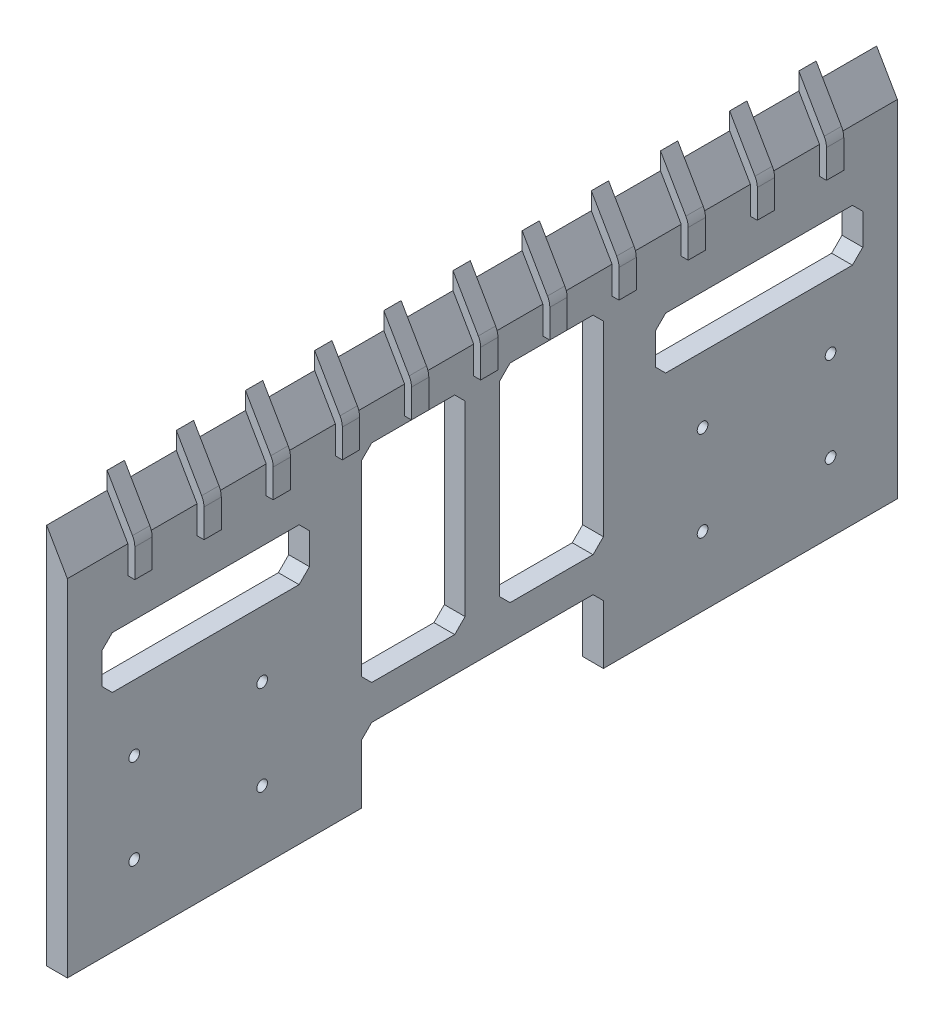
SolidWorks part; units mm, degrees
ref_plane "前视基准面" through (0, 0, 0) normal (0, 0, 1) x (1, 0, 0)
ref_plane "上视基准面" through (0, 0, 0) normal (0, 1, 0) x (1, 0, 0)
ref_plane "右视基准面" through (0, 0, 0) normal (1, 0, 0) x (0, 0, -1)
sketch "草图1" plane through (0, 0, 0) normal (1, 0, 0) x (0, 0, -1)
  line L1 (0, 0) -> (240, 0)
  line L2 (0, 0) -> (0, -100)
  line L3 (0, -100) -> (240, -100)
  line L4 (240, 0) -> (240, -100)
  dimension "D1" = 240
  dimension "D2" = 100
extrude "凸台-拉伸1" add sketch "草图1" along normal blind 6
sketch "草图2" plane through (6, 0, 0) normal (1, 0, 0) x (0, 0, -1)
  line L0 (0, 0) -> (0, -100) construction
  line L1 (19.3235, -54) -> (56.3235, -54) construction
  line L2 (19.3235, -54) -> (19.3235, -80) construction
  line L3 (19.3235, -80) -> (56.3235, -80) construction
  line L4 (56.3235, -54) -> (56.3235, -80) construction
  line L5 (240, 0) -> (0, 0) construction
  line L6 (120, 0) -> (120, -100) construction
  line L7 (0, -100) -> (240, -100) construction
  line L8 (183.6765, -54) -> (183.6765, -80) construction
  line L9 (220.6765, -80) -> (183.6765, -80) construction
  line L10 (220.6765, -54) -> (220.6765, -80) construction
  line L11 (220.6765, -54) -> (183.6765, -54) construction
  circle A0 centre (19.3235, -54) radius 1.55
  circle A1 centre (56.3235, -80) radius 1.55
  circle A2 centre (56.3235, -54) radius 1.55
  circle A3 centre (19.3235, -80) radius 1.55
  circle A4 centre (220.6765, -80) radius 1.55
  circle A5 centre (183.6765, -54) radius 1.55
  circle A6 centre (183.6765, -80) radius 1.55
  circle A7 centre (220.6765, -54) radius 1.55
  dimension "D5" = 3.1
  dimension "D1" = 19.3235
  dimension "D2" = 54
  dimension "D3" = 37
  dimension "D4" = 26
extrude "切除-拉伸1" cut sketch "草图2" against normal through all
sketch "草图3" plane through (6, 0, 0) normal (1, 0, 0) x (0, 0, -1)
  line L0 (120, 0) -> (120, -100) construction
  line L1 (10, -20) -> (70, -20)
  line L2 (10, -20) -> (10, -35)
  line L3 (10, -35) -> (70, -35)
  line L4 (70, -20) -> (70, -35)
  line L5 (240, 0) -> (0, 0) construction
  line L6 (0, -100) -> (240, -100) construction
  line L7 (0, 0) -> (0, -100) construction
  line L8 (170, -20) -> (170, -35)
  line L9 (230, -35) -> (170, -35)
  line L10 (230, -20) -> (230, -35)
  line L11 (230, -20) -> (170, -20)
  dimension "D1" = 10
  dimension "D2" = 20
  dimension "D3" = 15
  dimension "D4" = 60
extrude "切除-拉伸2" cut sketch "草图3" against normal through all
sketch "草图4" plane through (6, 0, 0) normal (1, 0, 0) x (0, 0, -1)
  line L0 (120, 0) -> (120, -100) construction
  line L1 (85, -10) -> (115, -10)
  line L2 (85, -10) -> (85, -70)
  line L3 (85, -70) -> (115, -70)
  line L4 (115, -10) -> (115, -70)
  line L5 (240, 0) -> (0, 0) construction
  line L6 (0, -100) -> (240, -100) construction
  line L7 (0, 0) -> (0, -100) construction
  line L8 (125, -10) -> (125, -70)
  line L9 (155, -70) -> (125, -70)
  line L10 (155, -10) -> (155, -70)
  line L11 (155, -10) -> (125, -10)
  dimension "D1" = 10
  dimension "D2" = 30
  dimension "D3" = 85
  dimension "D4" = 30
extrude "切除-拉伸3" cut sketch "草图4" against normal through all contours L4 L1 L2 L3 | L8 L9 L10 L11
sketch "草图5" plane through (0, 0, 0) normal (-1, 0, 0) x (0, 0, 1)
  circle A0 centre (-183.6765, -80) radius 3
  circle A1 centre (-220.6765, -80) radius 3
  circle A2 centre (-183.6765, -54) radius 3
  circle A3 centre (-220.6765, -54) radius 3
  circle A4 centre (-45, -80) radius 3
  circle A5 centre (-19.3235, -80) radius 3
  circle A6 centre (-19.3235, -54) radius 3
  circle A7 centre (-56.3235, -54) radius 3
  dimension "D1" = 6
extrude "切除-拉伸4" cut sketch "草图5" against normal blind 3
sketch "草图6" plane through (0, 0, 0) normal (0, 0, 1) x (1, 0, 0)
  line L0 (6, 0) -> (0, 0)
  line L1 (0, 0) -> (0, 10.3923)
  line L2 (0, 10.3923) -> (6, 0)
  dimension "D1" = 30
extrude "凸台-拉伸2" add sketch "草图6" against normal blind 240
ref_plane "基准面1" through (0, 0, -117.5) normal (0, 0, 1) x (1, 0, 0)
sketch "草图7" plane through (0, 0, -117.5) normal (0, 0, 1) x (1, 0, 0)
  line L0 (0, 10.3923) -> (0, 15.3923)
  line L1 (0, 15.3923) -> (8, 1.5359)
  line L2 (8, 1.5359) -> (8, -8)
  line L3 (8, -8) -> (6, -8)
  line L4 (6, 0) -> (6, -100) construction
  line L5 (6, -8) -> (6, 0)
  line L6 (6, 0) -> (0, 10.3923)
  dimension "D1" = 5
  dimension "D2" = 2
  dimension "D3" = 8
extrude "凸台-拉伸3" add sketch "草图7" against normal blind 5
pattern_linear "阵列(线性)5" count 6 spacing 20 along (0, 0, 1) count 6 spacing 20 along (0, 0, -1) of "凸台-拉伸3"
fillet "圆角5" radius 5 11 edges at (8, 1.5359, -20) (8, 1.5359, -40) (8, 1.5359, -60) (8, 1.5359, -80) (8, 1.5359, -100) (8, 1.5359, -120) (8, 1.5359, -140) (8, 1.5359, -160) (8, 1.5359, -180) (8, 1.5359, -200) (8, 1.5359, -220)
chamfer "倒角1" distance 3 angle 45 16 edges at (3, -70, -85) (3, -70, -125) (3, -35, -170) (3, -35, -230) (3, -70, -155) (3, -70, -115) (3, -20, -230) (3, -10, -155) (3, -10, -115) (3, -20, -170) (3, -10, -125) (3, -10, -85) (3, -35, -70) (3, -20, -70) (3, -35, -10) (3, -20, -10)
sketch "草图8" plane through (6, 0, 0) normal (1, 0, 0) x (0, 0, -1)
  line L0 (85, -100) -> (85, -83)
  line L1 (0, -100) -> (240, -100) construction
  line L2 (88, -80) -> (152, -80)
  line L3 (155, -83) -> (155, -100)
  line L4 (155, -100) -> (85, -100)
  line L5 (85, -83) -> (88, -80)
  line L6 (152, -80) -> (155, -83)
  point P1 (85, -80)
  point P6 (155, -80)
extrude "切除-拉伸7" cut sketch "草图8" against normal through all
